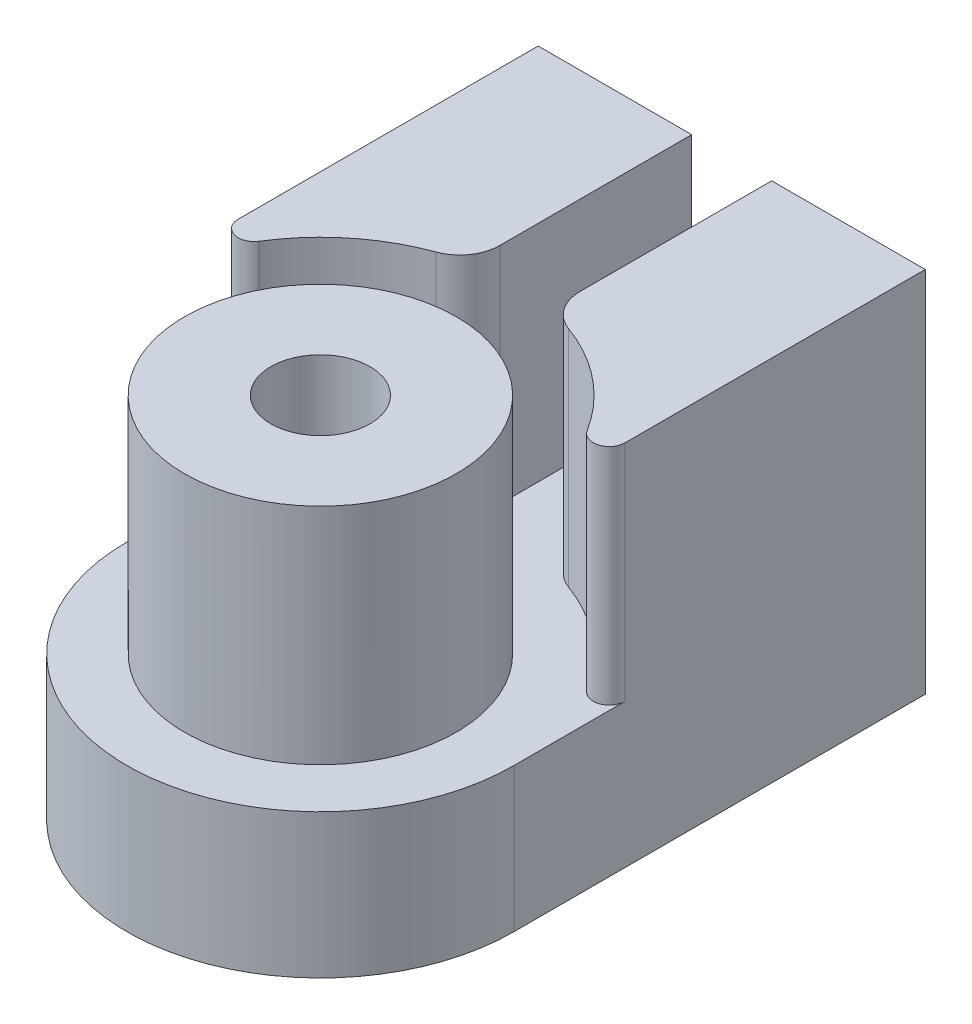
SolidWorks part; units mm, degrees
ref_plane "Front" through (0, 0, 0) normal (0, 0, 1) x (1, 0, 0)
ref_plane "Top" through (0, 0, 0) normal (0, 1, 0) x (1, 0, 0)
ref_plane "Right" through (0, 0, 0) normal (1, 0, 0) x (0, 0, -1)
sketch "Sketch1" plane through (0, 0, 0) normal (0, 1, 0) x (1, 0, 0)
  line L0 (0, 0) -> (0, 12.8586) construction
  line L1 (1.25, 6.8586) -> (1.25, 12.8586)
  line L2 (-1.25, 6.8586) -> (-1.25, 12.8586)
  line L3 (-1.25, 0) -> (-1.25, 12.8586) construction
  line L4 (1.25, 0) -> (1.25, 12.8586) construction
  line L5 (-6.05, 9.0067) -> (-6.05, 12.8586)
  line L6 (6.05, 9.0067) -> (6.05, 12.8586)
  line L7 (-6.05, 12.8586) -> (6.05, 12.8586)
  line L8 (-6.05, 0) -> (-6.05, 9.0067)
  line L9 (6.05, 0) -> (6.05, 9.0597)
  circle A0 centre (0, 0) radius 4.25
  arc A1 (-2.0719, 5.6842) -> (2.0719, 5.6842) centre (0, 0) ccw
  circle A2 centre (0, 0) radius 6.05 construction
  arc A3 (1.25, 6.8586) -> (2.0719, 5.6842) centre (2.5, 6.8586) ccw
  arc A4 (-1.25, 6.8586) -> (-2.0719, 5.6842) centre (-2.5, 6.8586) cw
  arc A5 (-6.05, 9.0067) -> (-6.05, 9.0067) centre (-6.05, 9.0067) cw
  arc A7 (6.05, 9.0067) -> (6.05, 9.0067) centre (6.05, 9.0067) ccw
  circle A8 centre (0, 0) radius 1.55
  arc A10 (-6.05, 9.0067) -> (6.05, 9.0067) centre (0, 0) ccw construction
  dimension "D1" = 8.5
  dimension "D6" = 1.25
  dimension "D8" = 3.1
  dimension "D3" = 6
  dimension "D4" = 1.25
  dimension "D2" = 1.8
  dimension "D5" = 1.25
extrude "Boss-Extrude1" add sketch "Sketch1" along normal blind 7
sketch "Sketch2" plane through (0, 0, 0) normal (0, -1, 0) x (1, 0, 0)
  line L0 (6.05, -12.8586) -> (1.25, -12.8586)
  line L1 (-1.25, -12.8586) -> (1.25, -12.8586)
  line L4 (1.25, -6.8586) -> (1.25, -12.8586)
  line L6 (6.05, -12.8586) -> (6.05, 0)
  line L7 (1.25, -12.8586) -> (6.05, -12.8586)
  line L8 (6.05, -12.8586) -> (6.05, 0)
  line L10 (6.05, -12.8586) -> (6.05, 0)
  line L11 (1.25, -6.8586) -> (1.25, -12.8586)
  line L13 (1.25, -12.8586) -> (6.05, -12.8586)
  line L18 (1.25, -12.8586) -> (6.05, -12.8586)
  line L19 (-6.05, 0) -> (-6.05, -12.8586)
  line L20 (6.05, -12.8586) -> (6.05, 0)
  line L21 (1.25, -6.8586) -> (1.25, -12.8586)
  line L22 (1.25, -12.8586) -> (6.05, -12.8586)
  line L24 (-6.05, -12.8586) -> (-1.25, -12.8586)
  line L25 (-1.25, -12.8586) -> (-1.25, -6.8586)
  line L26 (-6.05, 0) -> (-6.05, -12.8586)
  line L27 (-6.05, -12.8586) -> (-1.25, -12.8586)
  line L28 (-1.25, -12.8586) -> (-1.25, -6.8586)
  line L29 (1.25, -6.8586) -> (1.25, -12.8586)
  line L30 (1.25, -12.8586) -> (6.05, -12.8586)
  line L31 (6.05, -12.8586) -> (6.05, 0)
  line L32 (1.25, -6.8586) -> (1.25, -12.8586)
  line L33 (1.25, -12.8586) -> (6.05, -12.8586)
  line L34 (6.05, -12.8586) -> (6.05, 0)
  circle A0 centre (0, 0) radius 1.55 construction
  circle A1 centre (0, 0) radius 1.55
  arc A2 (6.05, 0) -> (2.0719, -5.6842) centre (0, 0) ccw
  arc A4 (2.0719, -5.6842) -> (1.25, -6.8586) centre (2.5, -6.8586) ccw
  arc A5 (2.0719, -5.6842) -> (6.05, 0) centre (0, 0) ccw
  arc A7 (-1.25, -6.8586) -> (-2.0719, -5.6842) centre (-2.5, -6.8586) ccw
  arc A12 (2.0719, -5.6842) -> (6.05, 0) centre (0, 0) ccw
  arc A13 (2.0719, -5.6842) -> (1.25, -6.8586) centre (2.5, -6.8586) ccw
  arc A14 (-6.05, 0) -> (-2.0719, -5.6842) centre (0, 0) ccw
  arc A18 (-1.25, -6.8586) -> (-2.0719, -5.6842) centre (-2.5, -6.8586) ccw
  arc A19 (-6.05, 0) -> (-2.0719, -5.6842) centre (0, 0) ccw
  arc A20 (2.0719, -5.6842) -> (6.05, 0) centre (0, 0) ccw
  arc A21 (2.0719, -5.6842) -> (1.25, -6.8586) centre (2.5, -6.8586) ccw
  arc A22 (2.0719, -5.6842) -> (6.05, 0) centre (0, 0) ccw
  arc A23 (2.0719, -5.6842) -> (1.25, -6.8586) centre (2.5, -6.8586) ccw
  line M13 (1.25, -12.8586) -> (6.05, -12.8586)
  arc M16 (6.05, 0) -> (2.0719, -5.6842) centre (0, 0) cw
  arc M17 (2.0719, -5.6842) -> (1.25, -6.8586) centre (2.5, -6.8586) ccw
  line M18 (1.25, -6.8586) -> (1.25, -12.8586)
  line M20 (6.05, -12.8586) -> (6.05, 0)
  dimension "D3" = 0
  dimension "D2" = 0
  dimension "D1" = 0
  dimension "D4" = 0
extrude "Boss-Extrude2" add sketch "Sketch2" along normal blind 4.5 contours L28 A18 A2 L26 L27 | M17 M18 M13 M20 M16 | A2 A1 M16 | A18 L28 L1 A2 M18 M17
fillet "Fillet1" radius 0.5 1 edges at (-6.05, 3.5, 0)
fillet "Fillet2" radius 0.5 1 edges at (6.05, 3.5, 0)
